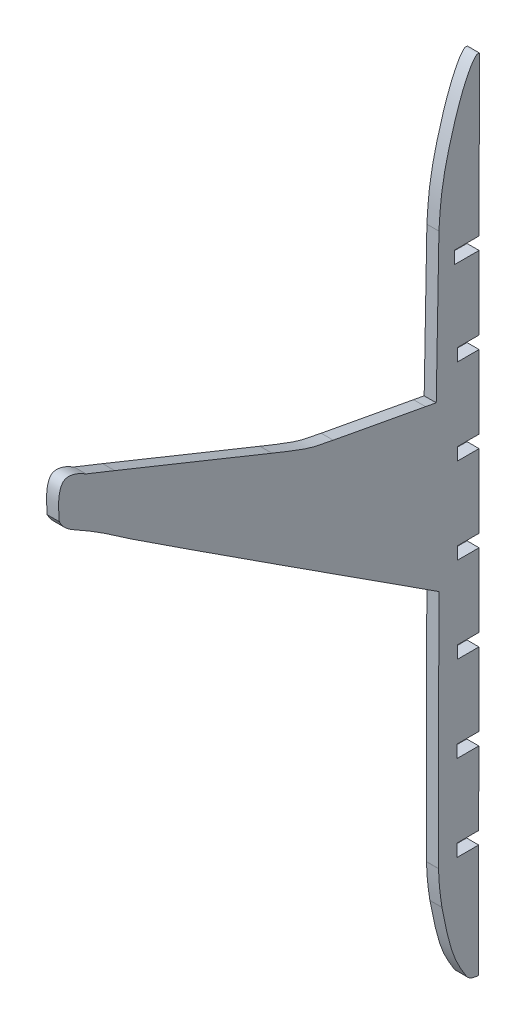
SolidWorks part; units mm, degrees
ref_plane "Alzado" through (0, 0, 0) normal (1, 0, 0) x (0, 1, 0)
ref_plane "Planta" through (0, 0, 0) normal (0, 0, 1) x (0, 1, 0)
ref_plane "Vista lateral" through (0, 0, 0) normal (0, 1, 0) x (-1, 0, 0)
sketch "Croquis1" plane through (0, 0, 0) normal (1, 0, 0) x (0, 1, 0)
  line L0 (50.0642, -47.0675) -> (50.0642, -41.5484)
  line L1 (50.0642, -41.5484) -> (47.2642, -41.5484)
  line L2 (47.2642, -41.5484) -> (47.2642, -47.0627)
  line L3 (47.2642, -47.0627) -> (30.8534, -47.0618)
  line L4 (30.8534, -47.0618) -> (30.8534, -42.2169)
  line L5 (30.8534, -42.2169) -> (28.0534, -42.2169)
  line L6 (28.0534, -42.2169) -> (28.0534, -47.0591)
  line L7 (28.0534, -47.0591) -> (11.6427, -47.0591)
  line L8 (11.6427, -47.0591) -> (11.6427, -42.2143)
  line L9 (11.6427, -42.2143) -> (8.8427, -42.2143)
  line L10 (8.8427, -42.2143) -> (8.8427, -47.0591)
  line L11 (8.8427, -47.0591) -> (-7.5893, -47.0591)
  line L12 (-7.5893, -47.0591) -> (-7.5893, -42.2246)
  line L13 (-7.5893, -42.2246) -> (-10.3893, -42.2246)
  line L14 (-10.3893, -42.2246) -> (-10.3893, -47.0652)
  line L15 (-10.3893, -47.0652) -> (-26.8, -47.0401)
  line L16 (-26.8, -47.0401) -> (-26.8, -42.191)
  line L17 (-26.8, -42.191) -> (-29.6, -42.191)
  line L18 (-29.6, -42.191) -> (-29.6, -47.0358)
  line L19 (-29.6, -47.0358) -> (-45.9886, -47.0108)
  line L20 (-45.9886, -47.0108) -> (-45.9886, -42.1617)
  line L21 (-45.9886, -42.1617) -> (-48.7886, -42.1617)
  line L22 (-48.7886, -42.1617) -> (-48.7886, -47.0065)
  line L23 (-48.7886, -47.0065) -> (-65.1778, -46.9815)
  line L24 (-65.1778, -46.9815) -> (-65.1778, -42.1315)
  line L25 (-65.1778, -42.1315) -> (-67.9778, -42.1315)
  line L26 (-67.9778, -42.1315) -> (-67.9778, -46.9771)
  line L27 (-67.9778, -46.9771) -> (-93.2778, -46.9771)
  line L28 (-68.0726, -37.9771) -> (-68.0362, -37.9771)
  line L29 (-68.0362, -37.9771) -> (-14.3778, -38.0591)
  line L30 (22.5123, -37.4725) -> (55.4965, -38.079)
  line L31 (85.5123, -47.1424) -> (50.0642, -47.0675)
  spline S0 degree 3 poles (-93.2778, -46.9771) (-93.1819, -46.1748) (-93.0624, -45.1747) (-92.3189, -44.4278) (-92.1058, -44.2716) (-92.045, -44.2271) knots 0 0 0 0 0.743763 0.927076 1 1 1 1
  spline S1 degree 3 poles (-92.045, -44.2271) (-90.7569, -43.4333) (-88.0569, -41.7694) (-82.578, -40.0345) (-78.4606, -39.2378) (-75.9649, -38.7549) knots 0 0 0 0 0.264368 0.554136 1 1 1 1
  spline S2 degree 3 poles (-75.9649, -38.7549) (-74.3455, -38.5123) (-71.7266, -38.12) (-69.0819, -38.0166) (-68.0726, -37.9771) knots 0 0 0 0 0.618393 1 1 1 1
  spline S3 degree 3 poles (-14.3778, -38.0591) (-9.4826, -30.4652) (-0.0883, -15.8917) (11.4013, 1.8973) (19.8394, 14.905) (25.2911, 23.2815) (28.674, 28.4254) (30.2091, 30.7596) knots 0 0 0 0 0.330543 0.634353 0.774759 0.897792 1 1 1 1
  spline S4 degree 3 poles (30.2091, 30.7596) (32.8257, 34.5034) (36.3799, 39.5887) (39.5819, 45.8279) (41.3609, 46.7696) (41.6591, 46.9275) knots 0 0 0 0 0.699057 0.949553 1 1 1 1
  spline S5 degree 3 poles (41.6591, 46.9275) (42.8011, 47.0077) (44.7178, 47.1424) (47.2114, 46.9793) (49.6111, 46.0466) (49.2528, 43.1701) (48.391, 41.7037) (47.9113, 40.8874) knots 0 0 0 0 0.262398 0.440379 0.595478 0.774813 1 1 1 1
  spline S6 degree 3 poles (47.9113, 40.8874) (47.8625, 40.7356) (47.7937, 40.5213) (47.5121, 39.8614) (46.7111, 37.8944) (45.9481, 35.9823) (45.3676, 34.5275) knots 0 0 0 0 0.069772 0.098492 0.314069 1 1 1 1
  spline S7 degree 3 poles (45.3676, 34.5275) (44.1115, 31.4331) (41.3837, 24.7133) (37.5555, 15.2434) (34.0659, 6.6006) (32.0479, 1.5832) (31.1352, -0.686) knots 0 0 0 0 0.263789 0.572839 0.806809 1 1 1 1
  spline S8 degree 3 poles (31.1352, -0.686) (30.6081, -1.9972) (29.7195, -4.2072) (28.6034, -7.09) (27.8254, -9.4) (27.274, -11.767) (26.9704, -13.4581) (26.8005, -14.4041) knots 0 0 0 0 0.293827 0.49526 0.642749 0.800166 1 1 1 1
  spline S9 degree 3 poles (26.8005, -14.4041) (26.4718, -16.1863) (25.7495, -20.1023) (24.7194, -25.6461) (23.7692, -30.7561) (23.215, -33.7329) (22.964, -35.081) knots 0 0 0 0 0.258532 0.568058 0.804378 1 1 1 1
  spline S10 degree 3 poles (22.964, -35.081) (22.8683, -35.5978) (22.7207, -36.3956) (22.5666, -37.192) (22.5123, -37.4725) knots 0 0 0 0 0.64787 1 1 1 1
  spline S11 degree 3 poles (55.4965, -38.079) (57.9279, -38.2307) (63.0022, -38.5473) (70.412, -40.2277) (77.16, -42.2327) (82.1196, -44.1876) (84.6282, -45.6509) (85.5928, -46.5654) (85.5353, -46.9775) (85.5123, -47.1424) knots 0 0 0 0 0.227073 0.473886 0.705747 0.886968 0.962929 0.985171 1 1 1 1
  dimension "D1" = 2.8
  dimension "D2" = 2.8
  dimension "D3" = 2.8
  dimension "D4" = 2.8
  dimension "D5" = 2.8
  dimension "D6" = 2.8
  dimension "D7" = 2.8
  dimension "D8" = 82
  dimension "D9" = 11.45
  dimension "D10" = 72
  dimension "D11" = 78.9
  dimension "D12" = 84.4
  dimension "D13" = 9
  dimension "D14" = 1.05
  dimension "D15" = 9
  dimension "D16" = 9
  dimension "D17" = 9
  dimension "D18" = 9
  dimension "D19" = 9
  dimension "D20" = 4.85
  dimension "D21" = 16.3892
  dimension "D22" = 25.3
  dimension "D23" = 9
  dimension "D24" = 9
extrude "Saliente-Extruir1" add sketch "Croquis1" along normal blind 2.7
